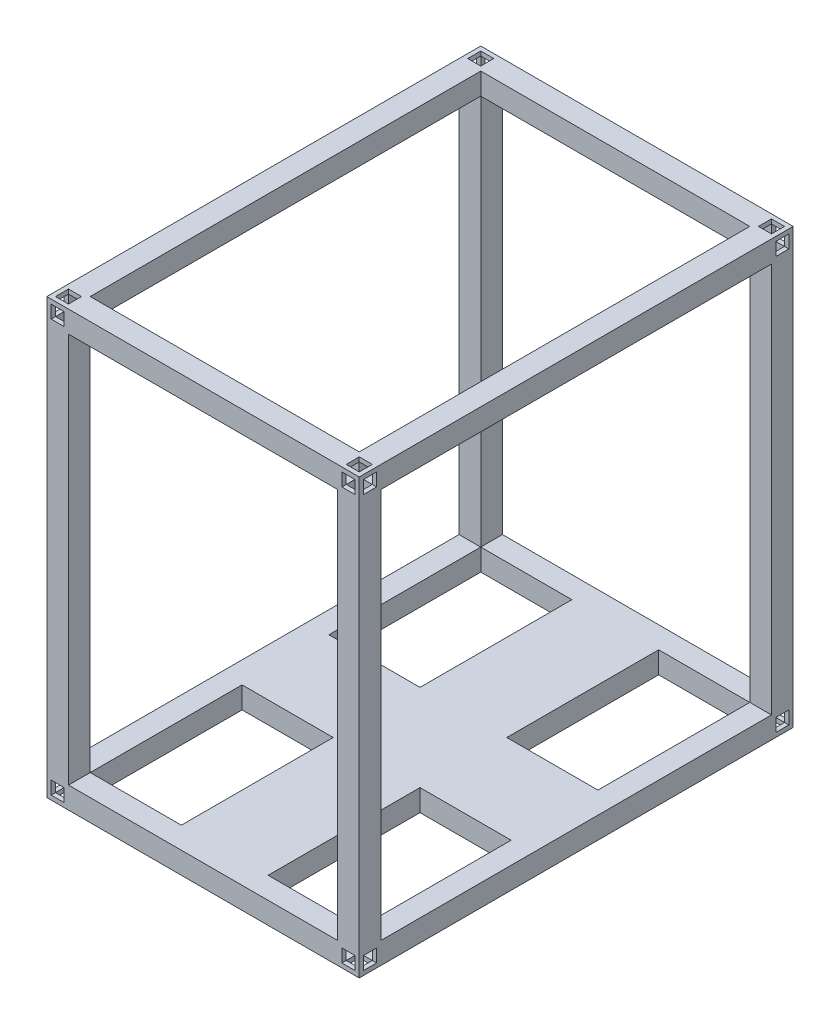
SolidWorks part; units mm, degrees
ref_plane "Front Plane" through (0, 0, 0) normal (0, 0, 1) x (1, 0, 0)
ref_plane "Top Plane" through (0, 0, 0) normal (0, 1, 0) x (1, 0, 0)
ref_plane "Right Plane" through (0, 0, 0) normal (1, 0, 0) x (0, 0, -1)
sketch "Sketch1" plane through (0, 0, 0) normal (0, 0, 1) x (1, 0, 0)
  line L1 (0, 0) -> (180, 0)
  line L2 (0, 0) -> (0, -250)
  line L3 (0, -250) -> (180, -250)
  line L4 (180, 0) -> (180, -250)
  dimension "D1" = 250
  dimension "D2" = 180
extrude "Boss-Extrude1" add sketch "Sketch1" along normal blind 250
sketch "Sketch2" plane through (0, 0, 0) normal (1, 0, 0) x (0, 0, -1)
  line L0 (-250, 0) -> (0, 0) construction
  line L1 (-237.5, -12.5) -> (-12.5, -12.5)
  line L2 (-237.5, -12.5) -> (-237.5, -237.5)
  line L3 (-237.5, -237.5) -> (-12.5, -237.5)
  line L4 (-12.5, -12.5) -> (-12.5, -237.5)
  line L5 (0, -250) -> (0, 0) construction
  line L6 (-250, -250) -> (0, -250) construction
  line L7 (-250, -250) -> (-250, 0) construction
  dimension "D1" = 12.5
  dimension "D2" = 12.5
  dimension "D3" = 12.5
  dimension "D4" = 12.5
extrude "Cut-Extrude2" cut sketch "Sketch2" along normal through all
sketch "Sketch3" plane through (0, 0, 250) normal (0, 0, 1) x (1, 0, 0)
  line L0 (180, -250) -> (180, 0) construction
  line L1 (12.5, -12.5) -> (167.5, -12.5)
  line L2 (12.5, -12.5) -> (12.5, -237.5)
  line L3 (12.5, -237.5) -> (167.5, -237.5)
  line L4 (167.5, -12.5) -> (167.5, -237.5)
  line L5 (0, -250) -> (180, -250) construction
  line L6 (0, 0) -> (0, -250) construction
  line L7 (180, 0) -> (0, 0) construction
  dimension "D1" = 12.5
  dimension "D2" = 12.5
  dimension "D3" = 12.5
  dimension "D4" = 12.5
extrude "Cut-Extrude3" cut sketch "Sketch3" against normal through all
sketch "Sketch4" plane through (0, 0, 0) normal (0, 1, 0) x (1, 0, 0)
  line L0 (180, 0) -> (0, 0) construction
  line L1 (12.5, -12.5) -> (167.5, -12.5)
  line L2 (12.5, -12.5) -> (12.5, -237.5)
  line L3 (12.5, -237.5) -> (167.5, -237.5)
  line L4 (167.5, -12.5) -> (167.5, -237.5)
  line L5 (180, -250) -> (180, 0) construction
  line L6 (180, -250) -> (0, -250) construction
  line L7 (0, -250) -> (0, 0) construction
  dimension "D1" = 12.5
  dimension "D2" = 12.5
  dimension "D3" = 12.5
  dimension "D4" = 12.5
extrude "Cut-Extrude4" cut sketch "Sketch4" against normal blind 250
sketch "Sketch7" plane through (0, 0, 0) normal (0, 0, 1) x (1, 0, 0)
  line L0 (0, 0) -> (0, -250) construction
  line L1 (2.5, -2.5) -> (10, -2.5)
  line L2 (2.5, -2.5) -> (2.5, -10)
  line L3 (2.5, -10) -> (10, -10)
  line L4 (10, -2.5) -> (10, -10)
  line L5 (180, 0) -> (0, 0) construction
  line L6 (12.5, -12.5) -> (12.5, -237.5) construction
  line L7 (167.5, -12.5) -> (12.5, -12.5) construction
  line L8 (177.5, -2.5) -> (177.5, -10)
  line L9 (170, -2.5) -> (170, -10)
  line L10 (170, -2.5) -> (177.5, -2.5)
  line L11 (170, -10) -> (177.5, -10)
  line L12 (177.5, -240) -> (177.5, -247.5)
  line L13 (170, -240) -> (170, -247.5)
  line L14 (170, -240) -> (177.5, -240)
  line L15 (170, -247.5) -> (177.5, -247.5)
  line L16 (10, -240) -> (10, -247.5)
  line L17 (2.5, -240) -> (2.5, -247.5)
  line L18 (2.5, -240) -> (10, -240)
  line L19 (2.5, -247.5) -> (10, -247.5)
  point P8 (10, -6.25)
  dimension "D1" = 2.5
  dimension "D2" = 2.5
  dimension "D3" = 2.5
  dimension "D4" = 2.5
  dimension "D5" = 2
  dimension "D6" = 2
extrude "Cut-Extrude6" cut sketch "Sketch7" along normal through all
sketch "Sketch8" plane through (0, 0, 0) normal (0, 1, 0) x (1, 0, 0)
  line L0 (180, 0) -> (0, 0) construction
  line L1 (2.5, -2.5) -> (10, -2.5)
  line L2 (2.5, -2.5) -> (2.5, -10)
  line L3 (2.5, -10) -> (10, -10)
  line L4 (10, -2.5) -> (10, -10)
  line L5 (12.5, -12.5) -> (12.5, -237.5) construction
  line L6 (167.5, -12.5) -> (12.5, -12.5) construction
  line L7 (0, -250) -> (0, 0) construction
  line L8 (177.5, -2.5) -> (177.5, -10)
  line L9 (170, -2.5) -> (170, -10)
  line L10 (170, -10) -> (177.5, -10)
  line L11 (170, -2.5) -> (177.5, -2.5)
  line L12 (177.5, -240) -> (177.5, -247.5)
  line L13 (170, -240) -> (170, -247.5)
  line L14 (170, -247.5) -> (177.5, -247.5)
  line L15 (170, -240) -> (177.5, -240)
  line L16 (10, -240) -> (10, -247.5)
  line L17 (2.5, -240) -> (2.5, -247.5)
  line L18 (2.5, -247.5) -> (10, -247.5)
  line L19 (2.5, -240) -> (10, -240)
  point P8 (6.25, -10)
  dimension "D1" = 2.5
  dimension "D2" = 2.5
  dimension "D3" = 2.5
  dimension "D4" = 2.5
  dimension "D5" = 2
  dimension "D6" = 2
extrude "Cut-Extrude7" cut sketch "Sketch8" against normal through all
sketch "Sketch9" plane through (0, 0, 0) normal (1, 0, 0) x (0, 0, -1)
  line L0 (-250, 0) -> (0, 0) construction
  line L1 (-2.5, -2.5) -> (-10, -2.5)
  line L2 (-2.5, -2.5) -> (-2.5, -10)
  line L3 (-2.5, -10) -> (-10, -10)
  line L4 (-10, -2.5) -> (-10, -10)
  line L5 (0, 0) -> (0, -250) construction
  line L6 (-12.5, -12.5) -> (-237.5, -12.5) construction
  line L7 (-12.5, -237.5) -> (-12.5, -12.5) construction
  line L8 (-240, -2.5) -> (-240, -10)
  line L9 (-240, -2.5) -> (-247.5, -2.5)
  line L10 (-247.5, -2.5) -> (-247.5, -10)
  line L11 (-240, -10) -> (-247.5, -10)
  line L12 (-240, -240) -> (-240, -247.5)
  line L13 (-240, -240) -> (-247.5, -240)
  line L14 (-247.5, -240) -> (-247.5, -247.5)
  line L15 (-240, -247.5) -> (-247.5, -247.5)
  line L16 (-2.5, -240) -> (-2.5, -247.5)
  line L17 (-2.5, -240) -> (-10, -240)
  line L18 (-10, -240) -> (-10, -247.5)
  line L19 (-2.5, -247.5) -> (-10, -247.5)
  dimension "D1" = 2.5
  dimension "D2" = 2.5
  dimension "D3" = 2.5
  dimension "D4" = 2.5
  dimension "D5" = 2
  dimension "D6" = 2
extrude "Cut-Extrude8" cut sketch "Sketch9" along normal blind 250
sketch "Sketch10" plane through (0, 0, 0) normal (0, 0, 1) x (1, 0, 0)
  line L0 (12.5, -237.5) -> (167.5, -237.5) construction
  line L1 (65, -237.5) -> (115, -237.5)
  line L2 (65, -237.5) -> (65, -250)
  line L3 (65, -250) -> (115, -250)
  line L4 (115, -237.5) -> (115, -250)
  line L5 (0, -250) -> (180, -250) construction
  line L6 (0, 0) -> (0, -250) construction
  dimension "D1" = 50
  dimension "D2" = 65
extrude "Boss-Extrude2" add sketch "Sketch10" along normal blind 250
sketch "Sketch12" plane through (180, 0, 0) normal (1, 0, 0) x (0, 0, -1)
  line L0 (-250, -250) -> (0, -250) construction
  line L1 (-150, -237.5) -> (-100, -237.5)
  line L2 (-150, -237.5) -> (-150, -250)
  line L3 (-150, -250) -> (-100, -250)
  line L4 (-100, -237.5) -> (-100, -250)
  line L5 (-250, -250) -> (-250, 0) construction
  dimension "D1" = 12.5
  dimension "D2" = 50
  dimension "D3" = 100
extrude "Boss-Extrude3" add sketch "Sketch12" against normal blind 180
